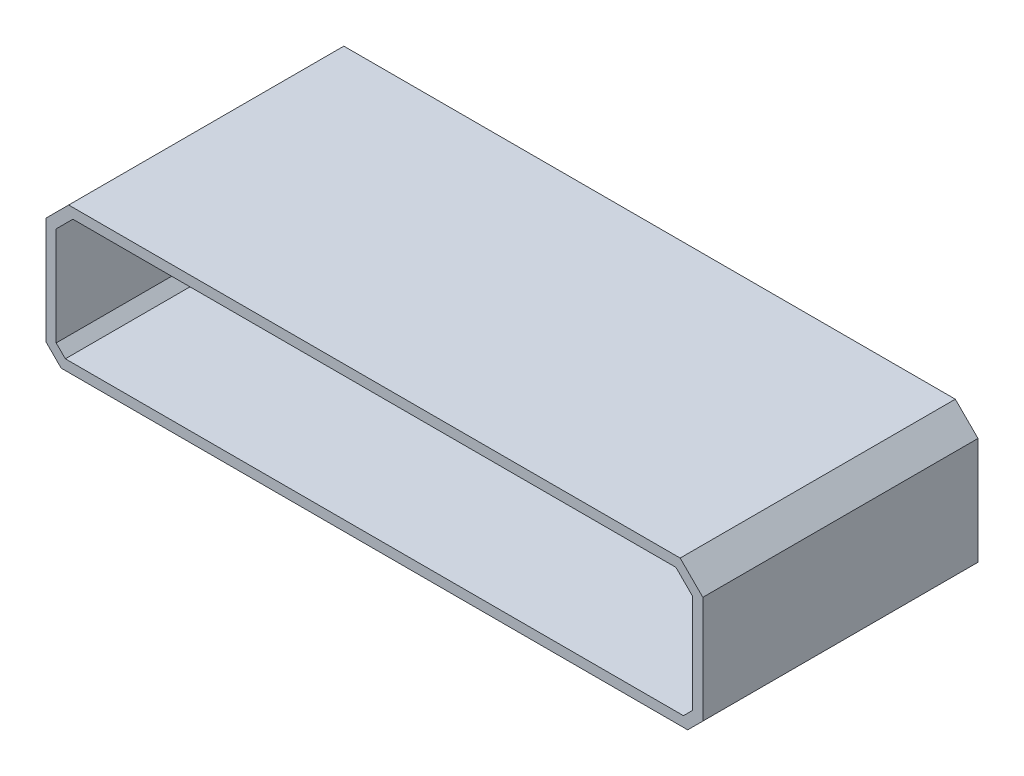
SolidWorks part; units mm, degrees
ref_plane "Front Plane" through (0, 0, 0) normal (0, 0, 1) x (1, 0, 0)
ref_plane "Top Plane" through (0, 0, 0) normal (0, 1, 0) x (1, 0, 0)
ref_plane "Right Plane" through (0, 0, 0) normal (1, 0, 0) x (0, 0, -1)
sketch "Sketch1" plane through (0, 0, 0) normal (0, 0, 1) x (1, 0, 0)
  line L0 (762, 0) -> (-762, 0)
  line L1 (-762, 0) -> (-818.4899, -56.4899)
  line L2 (-818.4899, -56.4899) -> (-818.4899, -323.7488)
  line L3 (-818.4899, -323.7488) -> (-780.7508, -361.4879)
  line L4 (-780.7508, -361.4879) -> (780.7508, -361.4879)
  line L5 (0, 287.6712) -> (0, -540.3433) construction
  line L6 (818.4899, -323.7488) -> (780.7508, -361.4879)
  line L7 (818.4899, -56.4899) -> (818.4899, -323.7488)
  line L8 (762, 0) -> (818.4899, -56.4899)
  line L9 (751.479, -25.4) -> (-751.479, -25.4)
  line L10 (-751.479, -25.4) -> (-793.0899, -67.0109)
  line L11 (-793.0899, -67.0109) -> (-793.0899, -313.2278)
  line L12 (-793.0899, -313.2278) -> (-770.2298, -336.0879)
  line L13 (-770.2298, -336.0879) -> (770.2298, -336.0879)
  line L14 (793.0899, -313.2278) -> (770.2298, -336.0879)
  line L15 (793.0899, -67.0109) -> (793.0899, -313.2278)
  line L16 (751.479, -25.4) -> (793.0899, -67.0109)
  point P10 (0, -361.4879)
  point P13 (0, 0)
  dimension "D1" = 1524
  dimension "D2" = 25.4
extrude "Boss-Extrude1" add sketch "Sketch1" along normal blind 685.8
